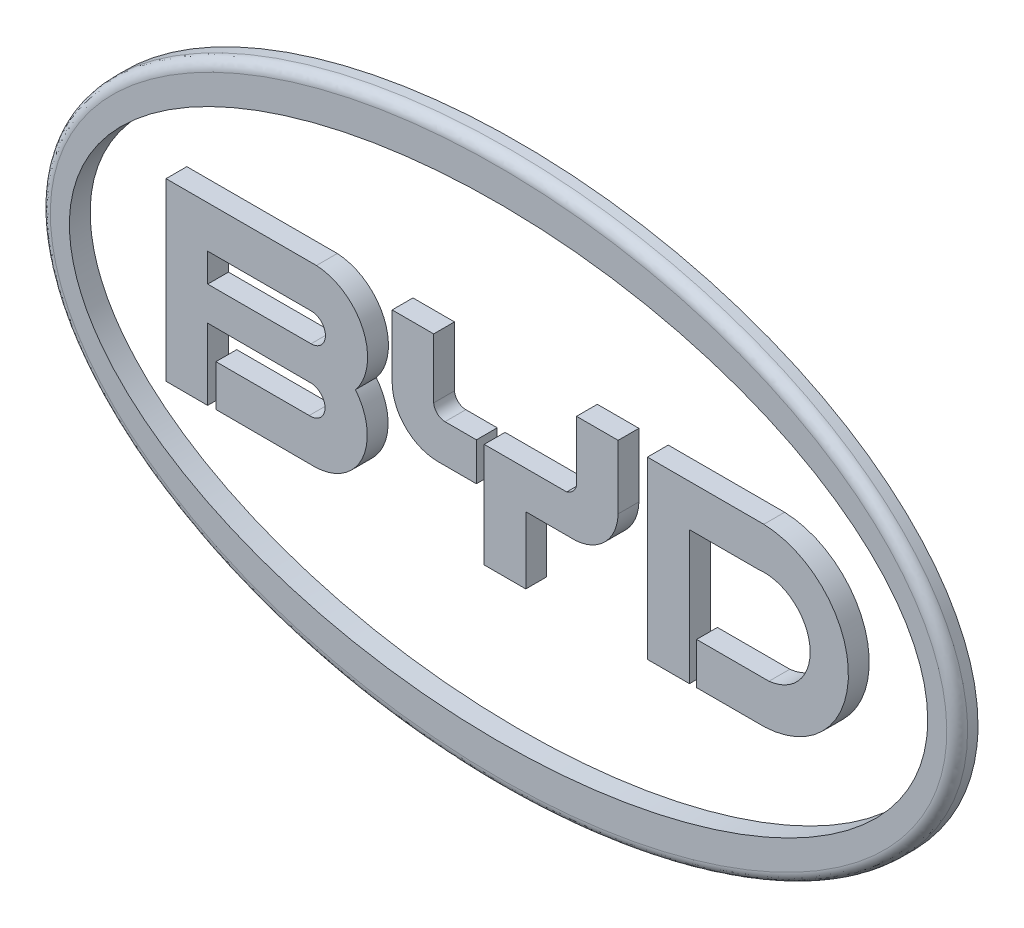
SolidWorks part; units mm, degrees
ref_plane "前视基准面" through (0, 0, 0) normal (0, 0, 1) x (1, 0, 0)
ref_plane "上视基准面" through (0, 0, 0) normal (0, 1, 0) x (1, 0, 0)
ref_plane "右视基准面" through (0, 0, 0) normal (1, 0, 0) x (0, 0, -1)
other "Configuration Table"
sketch "草图3" plane through (0, 0, 0) normal (0, 0, 1) x (1, 0, 0)
  line L0 (115.6969, 115.2379) -> (115.6986, 115.2379)
  line L2 (85.8579, 123.7017) -> (85.8579, 106.8315)
  line L3 (85.8579, 106.8315) -> (89.8579, 106.8213)
  line L4 (89.8579, 106.8213) -> (89.8579, 113.6772)
  line L5 (89.8579, 113.6772) -> (99.8624, 113.6516)
  line L6 (90.6564, 110.8641) -> (99.8624, 110.8641)
  line L7 (90.6564, 110.8641) -> (90.6564, 106.8799)
  line L8 (90.6564, 106.8799) -> (100.2082, 106.8555)
  line L9 (89.8657, 119.6669) -> (89.8657, 116.9237)
  line L10 (89.8657, 116.9237) -> (99.7982, 116.9237)
  line L11 (89.8657, 119.6669) -> (99.8234, 119.6669)
  line L12 (85.8579, 123.7017) -> (100.3205, 123.7017)
  line L15 (107.5959, 123.6424) -> (111.5883, 123.6424)
  line L16 (111.5883, 123.6424) -> (111.5883, 117.8987)
  line L17 (107.5959, 123.6424) -> (107.5959, 117.6534)
  line L18 (112.679, 116.8781) -> (115.6969, 116.8781)
  line L19 (115.6969, 116.8781) -> (115.6969, 113.2163)
  line L20 (115.6969, 113.2163) -> (112.0263, 113.2163)
  line L21 (125.2826, 113.2641) -> (120.444, 113.2641)
  line L22 (120.444, 113.2641) -> (120.444, 106.8341)
  line L23 (120.444, 106.8341) -> (116.4463, 106.8341)
  line L24 (116.4463, 106.8341) -> (116.4463, 116.8736)
  line L25 (116.4463, 116.8736) -> (124.377, 116.8781)
  line L26 (125.3192, 117.8478) -> (125.3192, 123.6476)
  line L27 (125.3192, 123.6476) -> (129.3203, 123.6476)
  line L28 (129.3203, 123.6476) -> (129.3203, 117.5226)
  line L29 (143.8224, 110.843) -> (136.862, 110.843)
  line L30 (136.862, 110.843) -> (136.862, 106.8253)
  line L31 (136.862, 106.8253) -> (143.4094, 106.8253)
  line L32 (143.8991, 119.6394) -> (136.1794, 119.6394)
  line L33 (136.1794, 119.6394) -> (136.1794, 106.8149)
  line L34 (136.1794, 106.8149) -> (132.1372, 106.8149)
  line L35 (132.1372, 106.8149) -> (132.1372, 123.6607)
  line L36 (132.1372, 123.6607) -> (143.3261, 123.6607)
  arc A0 (99.6219, 110.8641) -> (99.629, 113.6522) centre (99.7422, 112.2579) ccw
  arc A1 (99.7982, 116.9237) -> (99.7974, 119.6669) centre (99.8104, 118.2953) ccw
  arc A5 (107.5959, 117.6534) -> (112.0263, 113.2163) centre (111.9964, 117.6167) ccw
  arc A6 (111.5883, 117.8987) -> (112.679, 116.8781) centre (112.6985, 117.992) ccw
  arc A8 (124.5477, 113.2641) -> (129.3203, 117.5226) centre (124.9151, 117.6559) ccw
  arc A9 (143.8224, 110.843) -> (142.8048, 119.6394) centre (143.3519, 115.2456) ccw
  arc A12 (124.377, 116.8781) -> (125.3192, 117.8478) centre (123.9301, 118.255) ccw
  arc A16 (104.0708, 115.2379) -> (100.3205, 123.7017) centre (100.0483, 118.5183) ccw
  arc A17 (99.8602, 106.8564) -> (104.0708, 115.2379) centre (100.0474, 112.0108) ccw
  arc A18 (115.6969, 115.2354) -> (115.6986, 115.2379) centre (111.9964, 117.6167) ccw
  arc A19 (143.4094, 106.8253) -> (143.3261, 123.6607) centre (143.0327, 115.2413) ccw
  ellipse E0 centre (117.8248, 115.2379) end of major axis (73.7348, 115.2379) minor radius 26.4432
  ellipse E1 centre (117.8248, 115.2379) end of major axis (159.0808, 115.2379) minor radius 22.4008
extrude "凸台-拉伸1" add sketch "草图3" along normal blind 2 contours E0 E1 | L8 A17 A16 L12 L2 L3 L4 L5 A0 L6 L7 A1 L10 L9 L11 | A6 L16 L15 L17 A5 L20 L19 L18 | A12 L25 L24 L23 L22 L21 A8 L28 L27 L26 | L31 A19 L36 L35 L34 L33 L32 A9 L29 L30
fillet "圆角1" radius 1 1 edges at (161.9149, 115.2379, 2)
